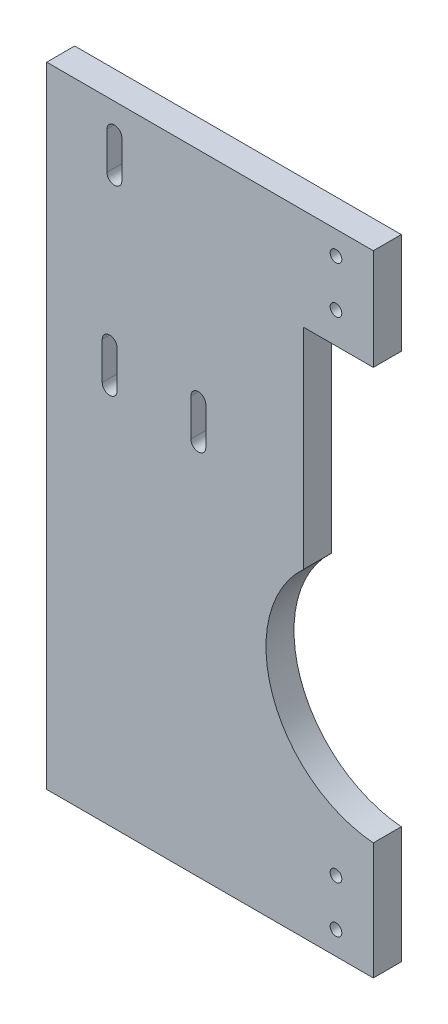
SolidWorks part; units mm, degrees
ref_plane "Plan de face" through (0, 0, 0) normal (0, 0, 1) x (1, 0, 0)
ref_plane "Plan de dessus" through (0, 0, 0) normal (0, 1, 0) x (1, 0, 0)
ref_plane "Plan de droite" through (0, 0, 0) normal (1, 0, 0) x (0, 0, -1)
sketch "Esquisse1" plane through (0, 0, 0) normal (0, 0, 1) x (1, 0, 0)
  line L0 (70, 67.5) -> (0, 67.5) construction
  line L1 (0, 0) -> (70, 0)
  line L2 (0, 0) -> (0, 135)
  line L3 (0, 135) -> (70, 135)
  line L4 (70, 0) -> (70, 135)
  circle A0 centre (62, 5) radius 1.25
  circle A1 centre (62, 15) radius 1.25
  circle A2 centre (62, 120) radius 1.25
  circle A3 centre (62, 130) radius 1.25
  point P7 (0, 0)
  dimension "D3" = 5
  dimension "D5" = 2
  dimension "D1" = 70
  dimension "D2" = 135
  dimension "D4" = 8
extrude "Boss.-Extru.1" add sketch "Esquisse1" along normal blind 6
sketch "Esquisse3" plane through (0, 0, 6) normal (0, 0, 1) x (1, 0, 0)
  line L0 (0, 0) -> (70, 0) construction
  line L1 (70, 0) -> (70, 135) construction
  line L2 (70, 25.0801) -> (70, 113.3303)
  line L3 (70, 113.3303) -> (55, 113.3303)
  line L4 (55, 113.3303) -> (55, 68.3303)
  arc A1 (70, 25.0801) -> (55, 68.3303) centre (72, 50) cw
  dimension "D2" = 25
  dimension "D1" = 50
  dimension "D3" = 2
  dimension "D4" = 45
  dimension "D5" = 15
extrude "Enlèv. mat.-Extru.2" cut sketch "Esquisse3" against normal through all
sketch "Esquisse4" plane through (0, 0, 0) normal (0, 0, -1) x (-1, 0, 0)
  line L0 (-14.5, 129) -> (-14.5, 121) construction
  line L1 (-12.9, 129) -> (-12.9, 121)
  line L2 (-16.1, 129) -> (-16.1, 121)
  line L4 (-13.5, 89.5) -> (-13.5, 81.5) construction
  line L5 (-11.9, 89.5) -> (-11.9, 81.5)
  line L6 (-15.1, 89.5) -> (-15.1, 81.5)
  line L7 (-32.5, 88.5) -> (-32.5, 80.5) construction
  line L8 (-30.9, 88.5) -> (-30.9, 80.5)
  line L9 (-34.1, 88.5) -> (-34.1, 80.5)
  circle A0 centre (-13.5, 86.5) radius 1.6 construction
  circle A1 centre (-32.5, 85.5) radius 1.6 construction
  circle A2 centre (-14.5, 126) radius 1.6 construction
  arc A3 (-12.9, 129) -> (-16.1, 129) centre (-14.5, 129) ccw
  arc A4 (-16.1, 121) -> (-12.9, 121) centre (-14.5, 121) ccw
  arc A5 (-11.9, 89.5) -> (-15.1, 89.5) centre (-13.5, 89.5) ccw
  arc A6 (-15.1, 81.5) -> (-11.9, 81.5) centre (-13.5, 81.5) ccw
  arc A7 (-30.9, 88.5) -> (-34.1, 88.5) centre (-32.5, 88.5) ccw
  arc A8 (-34.1, 80.5) -> (-30.9, 80.5) centre (-32.5, 80.5) ccw
  point P11 (-14.5, 125)
  point P18 (-13.5, 85.5)
  point P25 (-32.5, 84.5)
  dimension "D1" = 1.6
  dimension "D4" = 1.6
  dimension "D7" = 1.6
  dimension "D2" = 3
  dimension "D3" = 5
  dimension "D5" = 3
  dimension "D6" = 5
  dimension "D8" = 3
  dimension "D9" = 5
extrude "Enlèv. mat.-Extru.3" cut sketch "Esquisse4" against normal through all
